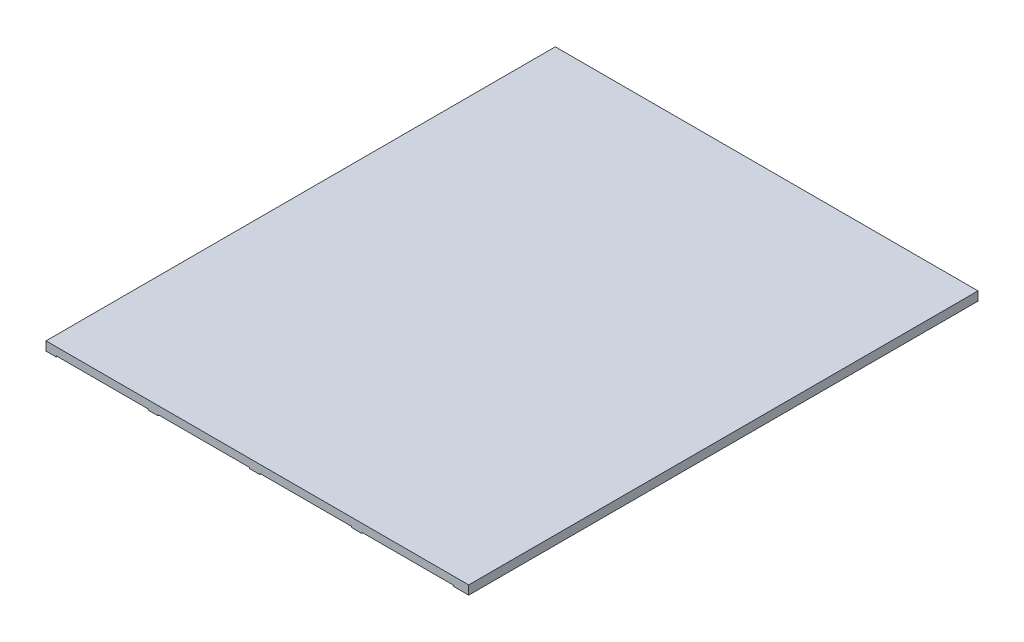
SolidWorks part; units mm, degrees
material "6061-T6 (SS)"
ref_plane "Front Plane" through (0, 0, 0) normal (0, 0, 1) x (1, 0, 0)
ref_plane "Top Plane" through (0, 0, 0) normal (0, 1, 0) x (1, 0, 0)
ref_plane "Right Plane" through (0, 0, 0) normal (1, 0, 0) x (0, 0, -1)
sketch "Sketch2" plane through (0, 0, 0) normal (0, 1, 0) x (1, 0, 0)
  line L1 (-41.5, -50) -> (41.5, -50)
  line L2 (-41.5, -50) -> (-41.5, 50)
  line L3 (-41.5, 50) -> (41.5, 50)
  line L4 (41.5, -50) -> (41.5, 50)
  line L5 (-41.5, -50) -> (41.5, 50) construction
  line L6 (-41.5, 50) -> (41.5, -50) construction
  point P0 (0, 0)
  dimension "D1" = 83
  dimension "D2" = 100
extrude "Boss-Extrude1" add sketch "Sketch2" along normal blind 1.75
sketch "Sketch3" plane through (0, 0, 0) normal (0, 1, 0) x (1, 0, 0)
  line L5 (-41.5, 50) -> (-41.5, -50) construction
  line L6 (-39.5, 30) -> (-21.5, 30)
  line L7 (-39.5, 30) -> (-39.5, 48)
  line L8 (-39.5, 48) -> (-21.5, 48)
  line L9 (-21.5, 30) -> (-21.5, 48)
  line L10 (-39.5, 30) -> (-21.5, 48) construction
  line L11 (-39.5, 48) -> (-21.5, 30) construction
  line L12 (41.5, 50) -> (-41.5, 50) construction
  point P0 (-30.5, 39)
  dimension "D1" = 18
  dimension "D2" = 2
  dimension "D3" = 2
extrude "Cut-Extrude5" cut sketch "Sketch3" along normal blind 0.2 contours L9 L8 L7 L6
pattern_linear "LPattern1" count 4 spacing 20 along (1, 0, 0) count 5 spacing 20 along (0, 0, 1) of "Cut-Extrude5"
